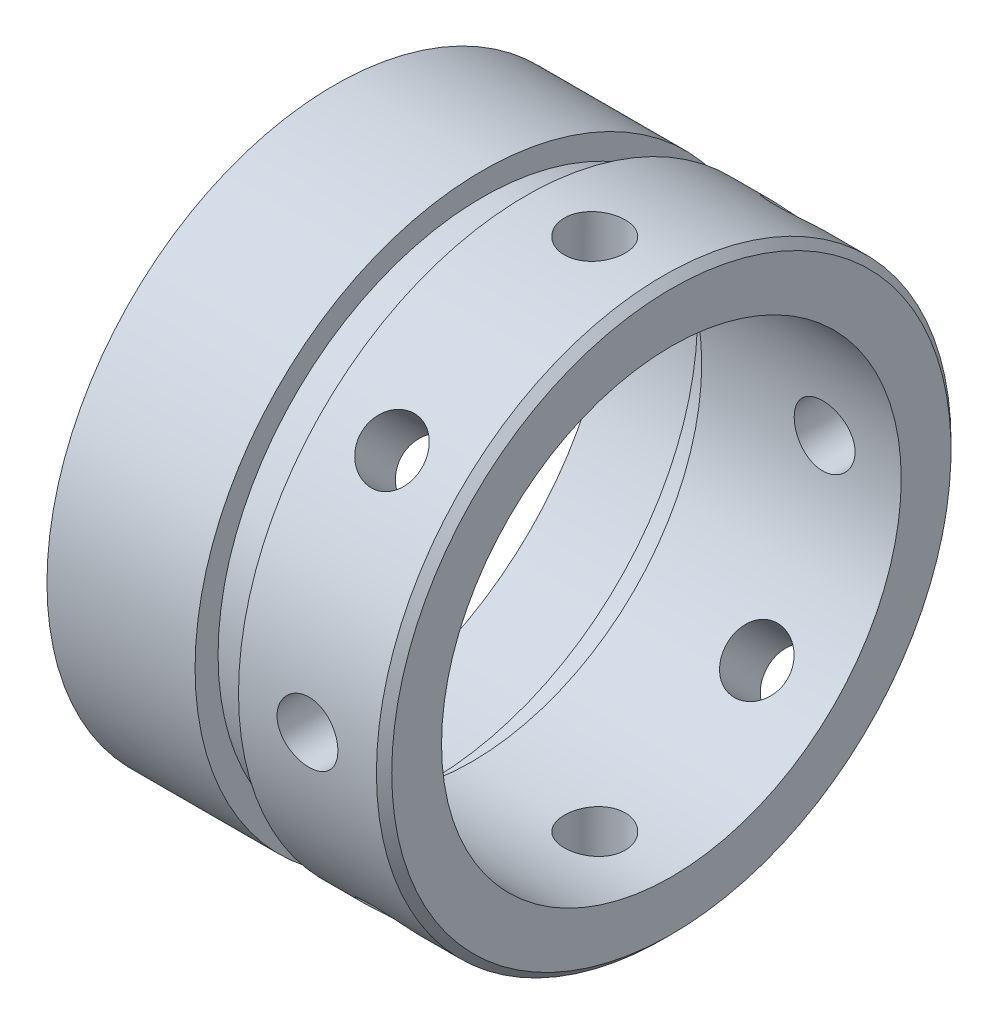
SolidWorks part; units mm, degrees
material "6061-T6 (SS)"
ref_plane "Front Plane" through (0, 0, 0) normal (0, 0, 1) x (1, 0, 0)
ref_plane "Top Plane" through (0, 0, 0) normal (0, 1, 0) x (1, 0, 0)
ref_plane "Right Plane" through (0, 0, 0) normal (1, 0, 0) x (0, 0, -1)
sketch "Sketch1" plane through (0, 0, 0) normal (0, 0, 1) x (1, 0, 0)
  line L0 (0, 0) -> (104.8766, 0) construction
  line L3 (0, 45.9613) -> (15.6972, 45.9613)
  line L4 (15.6972, 45.9613) -> (15.6972, 44.5089)
  line L6 (22.8092, 41.783) -> (22.8092, 38.1)
  line L7 (22.8092, 38.1) -> (55.88, 38.1)
  line L11 (54.61, 47.625) -> (31.75, 47.625)
  line L12 (0, 47.625) -> (0, 45.9613)
  line L13 (15.6972, 44.5089) -> (20.0876, 44.5089)
  line L14 (20.6972, 43.8993) -> (20.6972, 41.783)
  line L15 (20.6972, 41.783) -> (22.8092, 41.783)
  line L16 (24.5491, 47.625) -> (24.5491, 43.815)
  line L17 (24.5491, 43.815) -> (31.75, 43.815)
  line L18 (31.75, 43.815) -> (31.75, 47.625)
  line L19 (24.5491, 47.625) -> (0, 47.625)
  line L20 (55.88, 38.1) -> (55.88, 46.355)
  line L21 (55.88, 46.355) -> (54.61, 47.625)
  arc A0 (20.0876, 44.5089) -> (20.6972, 43.8993) centre (20.0876, 43.8993) cw
  point P13 (20.6972, 44.5089)
  point P14 (55.88, 47.625)
  dimension "D12" = 0.6096
  dimension "D1" = 104.8766
  dimension "D2" = 45.9613
  dimension "D3" = 7.112
  dimension "D4" = 41.783
  dimension "D5" = 38.1
  dimension "D6" = 24.13
  dimension "D7" = 5
  dimension "D8" = 2.7259
  dimension "D9" = 82.0674
  dimension "D10" = 47.625
  dimension "D11" = 1.27
  dimension "D13" = 7.2009
  dimension "D14" = 43.815
  dimension "D15" = 31.75
  dimension "D16" = 45
revolve "Revolve1" add sketch "Sketch1" angle 360 about L0
sketch "Sketch2" plane through (0, 0, 0) normal (0, 0, 1) x (1, 0, 0)
  line L0 (54.61, 0) -> (31.75, 0) construction
  line L1 (54.61, 47.625) -> (54.61, -47.625) construction
  line L2 (31.75, 47.625) -> (31.75, -47.625) construction
  line L3 (0, 47.625) -> (0, -47.625) construction
  point P0 (43.18, 0)
  point P9 (43.18, 0)
  point P12 (43.18, 0)
  dimension "D1" = 43.18
hole_wizard "Tap Drill for 3/8 Helicoil1" positions "Sketch2" profile "Sketch4" hole size "3/8-16" standard "ANSI Inch"
sketch "Sketch4" plane through (43.18, 0, 0) normal (1, 0, 0) x (0, 1, 0)
  line L0 (0, 0) -> (0, 47.625)
  line L1 (0, 47.625) -> (5.0419, 47.625)
  line L2 (5.0419, 47.625) -> (5.0419, 0)
  line L5 (5.0419, 0) -> (0, 0)
  line L11 (0, -6.35) -> (0, 107.95) construction
  dimension "Thru Hole Dia." = 10.0838
  dimension "Thru Hole Depth" = 47.625
pattern_circular "CirPattern1" count 8 over 360 about axis through (54.61, 0, 0) along (-1, 0, 0) of "Tap Drill for 3/8 Helicoil1"
